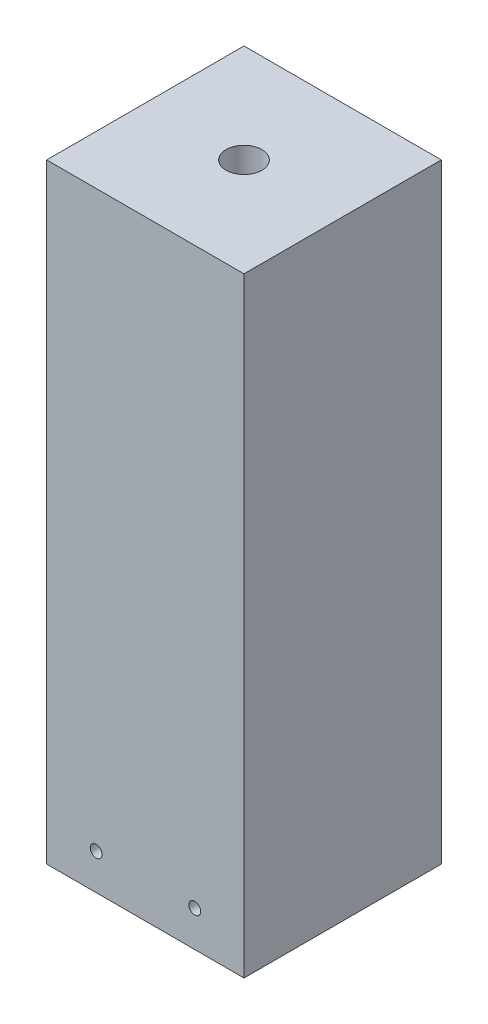
SolidWorks part; units mm, degrees
ref_plane "Front Plane" through (0, 0, 0) normal (0, 0, 1) x (1, 0, 0)
ref_plane "Top Plane" through (0, 0, 0) normal (0, 1, 0) x (1, 0, 0)
ref_plane "Right Plane" through (0, 0, 0) normal (1, 0, 0) x (0, 0, -1)
sketch "Sketch1" plane through (0, 0, 0) normal (0, 1, 0) x (1, 0, 0)
  line L1 (-27.5, 27.5) -> (27.5, 27.5)
  line L2 (-27.5, 27.5) -> (-27.5, -27.5)
  line L3 (-27.5, -27.5) -> (27.5, -27.5)
  line L4 (27.5, 27.5) -> (27.5, -27.5)
  line L5 (-27.5, 27.5) -> (27.5, -27.5) construction
  line L6 (-27.5, -27.5) -> (27.5, 27.5) construction
  point P0 (0, 0)
  dimension "D1" = 55
  dimension "D2" = 55
extrude "Boss-Extrude1" add sketch "Sketch1" along normal blind 170
sketch "Sketch2" plane through (0, 0, 0) normal (0, 1, 0) x (1, 0, 0)
  line L1 (-23, 23) -> (23, 23)
  line L2 (-23, 23) -> (-23, -23)
  line L3 (-23, -23) -> (23, -23)
  line L4 (23, 23) -> (23, -23)
  line L5 (-23, 23) -> (23, -23) construction
  line L6 (-23, -23) -> (23, 23) construction
  point P0 (0, 0)
  dimension "D1" = 46
  dimension "D2" = 46
  dimension "D3" = 46
  dimension "D4" = 46
extrude "Cut-Extrude4" cut sketch "Sketch2" along normal blind 160
sketch "Sketch5" plane through (-27.5, 0, 0) normal (-1, 0, 0) x (0, 0, 1)
  line L1 (-27.5, 0) -> (27.5, 0) construction
  line L2 (-7.5, 148.1754) -> (-7.5, 143.1754)
  line L3 (7.5, 148.1754) -> (7.5, 143.1754)
  line L4 (-7.5, 148.1754) -> (7.5, 148.1754)
  line L5 (7.5, 143.1754) -> (-7.5, 143.1754)
  point P0 (0, 0)
  point P1 (0, 148.1754)
  point P3 (-7.5, 148.1754)
  point P4 (7.5, 148.1754)
  point P9 (-7.5, 0)
  point P10 (7.5, 0)
  point P13 (-7.5, 143.1754)
  point P16 (7.5, 143.1754)
  dimension "D1" = 15
  dimension "D3" = 5
  dimension "D4" = 5
extrude "Cut-Extrude5" cut sketch "Sketch5" against normal up to surface (4.5 mm away) up to face at (-23, 80, 0)
sketch "Sketch6" plane through (0, 0, -27.5) normal (0, 0, -1) x (-1, 0, 0)
  line L0 (-27.5, 0) -> (27.5, 0) construction
  point P0 (0, 0)
  point P1 (0, 10)
  point P3 (-27.5, 0)
  point P4 (27.5, 0)
  point P6 (-13.784, 0)
  point P8 (13.716, 0)
  point P11 (-13.784, 10)
  point P12 (13.716, 10)
  dimension "D1" = 10
  dimension "D2" = 13.716
  dimension "D3" = 13.716
  dimension "D4" = 13.784
hole_wizard "Tap Drill for M4 Tap1" positions "3DSketch1" profile "Sketch7" hole size "M4" standard "ISO" end condition through all
sketch3d "3DSketch1"
  point P0 (13.784, 10, -27.5)
  point P3 (-13.716, 10, -27.5)
  dimension "D1" = 13.716
sketch "Sketch7" plane through (13.784, 10, -27.5) normal (1, 0, 0) x (0, 1, 0)
  line L0 (0, 0) -> (0, 55)
  line L1 (0, 55) -> (1.65, 55)
  line L2 (1.65, 55) -> (1.65, 0.025)
  line L3 (1.65, 0.025) -> (1.675, 0)
  line L5 (1.675, 0) -> (0, 0)
  line L6 (-1.65, 0.025) -> (-1.675, 0) construction
  line L11 (0, -6.35) -> (0, 107.95) construction
  dimension "Thru Hole Dia." = 3.3
  dimension "Thru Hole Depth" = 55
  dimension "Near C'Sink Dia." = 3.35
  dimension "Near C'Sink Angle" = 90
sketch "Sketch8" plane through (0, 170, 0) normal (0, 1, 0) x (1, 0, 0)
  circle A0 centre (0, 0) radius 5
extrude "Cut-Extrude6" cut sketch "Sketch8" along direction (0, 1, 0) on the side against the normal through all
sketch "Sketch10" plane through (0, 0, 27.5) normal (0, 0, 1) x (1, 0, 0)
  point P0 (0, 0)
  point P1 (-13.716, 0)
  point P3 (13.784, 0)
